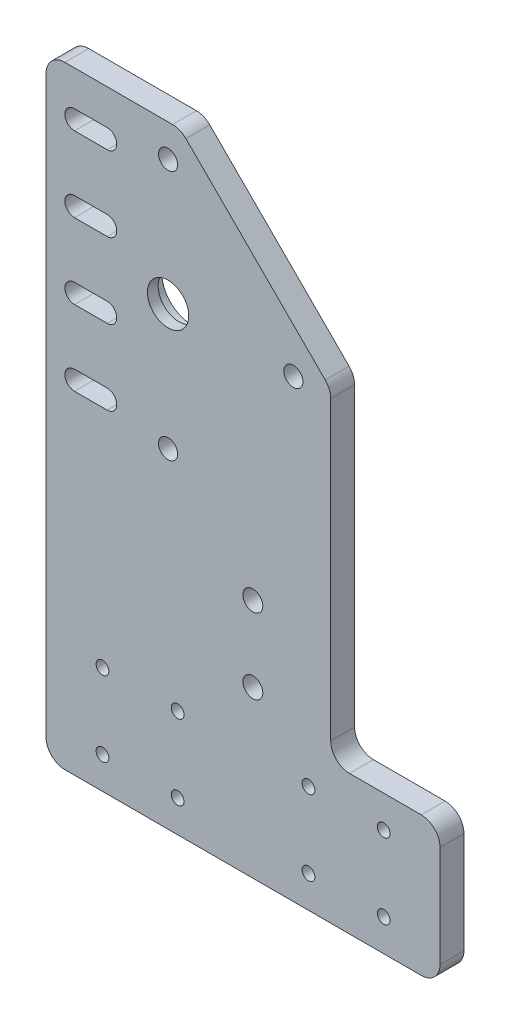
SolidWorks part; units mm, degrees
ref_plane "Alzado" through (0, 0, 0) normal (0, 0, 1) x (1, 0, 0)
ref_plane "Planta" through (0, 0, 0) normal (0, 1, 0) x (1, 0, 0)
ref_plane "Vista lateral" through (0, 0, 0) normal (1, 0, 0) x (0, 0, -1)
sketch "Croquis1" plane through (0, 0, 0) normal (0, 0, 1) x (1, 0, 0)
  line L0 (-57.45, 20) -> (-48.75, 20) construction
  line L1 (-65, -34) -> (-65, 86.95)
  line L3 (10.72, -29) -> (10.72, 49.8789)
  line L4 (15.72, -34) -> (34.8, -34)
  line L5 (34.8, -71) -> (-60, -71)
  line L6 (-50, -62.5) -> (-30, -62.5) construction
  line L7 (-50, -62.5) -> (-50, -42.5) construction
  line L8 (-50, -42.5) -> (-30, -42.5) construction
  line L9 (-30, -62.5) -> (-30, -42.5) construction
  line L10 (-50, -62.5) -> (-30, -42.5) construction
  line L11 (-50, -42.5) -> (-30, -62.5) construction
  line L12 (4.8, -62.5) -> (24.8, -62.5) construction
  line L13 (4.8, -62.5) -> (4.8, -42.5) construction
  line L14 (4.8, -42.5) -> (24.8, -42.5) construction
  line L15 (24.8, -62.5) -> (24.8, -42.5) construction
  line L16 (4.8, -62.5) -> (24.8, -42.5) construction
  line L17 (4.8, -42.5) -> (24.8, -62.5) construction
  line L18 (0, -34) -> (-33, -34) construction
  line L19 (0, -34) -> (0, 0) construction
  line L20 (0, 0) -> (-33, 0) construction
  line L21 (-33, -34) -> (-33, 0) construction
  line L24 (-57.45, 22.55) -> (-48.75, 22.55)
  line L29 (-65, -34) -> (-65, -66)
  line L30 (39.8, -39) -> (39.8, -66)
  line L31 (-57.45, 17.45) -> (-48.75, 17.45)
  line L32 (-57.45, 80) -> (-48.75, 80) construction
  line L33 (-57.45, 82.55) -> (-48.75, 82.55)
  line L34 (-57.45, 77.45) -> (-48.75, 77.45)
  line L35 (-60, 91.95) -> (-31.3511, 91.95)
  line L36 (-27.8155, 90.4855) -> (9.2555, 53.4145)
  line L37 (-57.45, 60) -> (-48.75, 60) construction
  line L38 (-57.45, 62.55) -> (-48.75, 62.55)
  line L39 (-57.45, 57.45) -> (-48.75, 57.45)
  line L40 (-57.45, 40) -> (-48.75, 40) construction
  line L41 (-57.45, 42.55) -> (-48.75, 42.55)
  line L42 (-57.45, 37.45) -> (-48.75, 37.45)
  line L43 (-32.55, 16.667) -> (-32.55, 83.333) construction
  line L44 (-32.55, 16.667) -> (0.783, 50) construction
  line L45 (0.783, 50) -> (-32.55, 83.333) construction
  line L46 (-32.55, 50) -> (0.783, 50) construction
  circle A0 centre (-50, -42.5) radius 1.7
  circle A1 centre (-30, -42.5) radius 1.7
  circle A2 centre (-30, -62.5) radius 1.7
  circle A3 centre (-50, -62.5) radius 1.7
  circle A4 centre (4.8, -62.5) radius 1.7
  circle A5 centre (4.8, -42.5) radius 1.7
  circle A6 centre (24.8, -42.5) radius 1.7
  circle A7 centre (24.8, -62.5) radius 1.7
  circle A8 centre (-10, -7) radius 2.65
  circle A9 centre (-10, -27) radius 2.65
  arc A22 (-60, -71) -> (-65, -66) centre (-60, -66) cw
  arc A23 (34.8, -71) -> (39.8, -66) centre (34.8, -66) ccw
  arc A24 (34.8, -34) -> (39.8, -39) centre (34.8, -39) cw
  arc A25 (10.72, -29) -> (15.72, -34) centre (15.72, -29) ccw
  arc A26 (-57.45, 22.55) -> (-57.45, 17.45) centre (-57.45, 20) ccw
  arc A27 (-48.75, 17.45) -> (-48.75, 22.55) centre (-48.75, 20) ccw
  arc A28 (-57.45, 82.55) -> (-57.45, 77.45) centre (-57.45, 80) ccw
  arc A29 (-48.75, 77.45) -> (-48.75, 82.55) centre (-48.75, 80) ccw
  circle A30 centre (-32.55, 50) radius 5.5
  circle A31 centre (-32.55, 16.667) radius 2.55
  circle A32 centre (-32.55, 83.333) radius 2.55
  circle A33 centre (0.783, 50) radius 2.55
  arc A34 (9.2555, 53.4145) -> (10.72, 49.8789) centre (5.72, 49.8789) cw
  arc A35 (-27.8155, 90.4855) -> (-31.3511, 91.95) centre (-31.3511, 86.95) ccw
  arc A36 (-65, 86.95) -> (-60, 91.95) centre (-60, 86.95) cw
  arc A37 (-57.45, 62.55) -> (-57.45, 57.45) centre (-57.45, 60) ccw
  arc A38 (-48.75, 57.45) -> (-48.75, 62.55) centre (-48.75, 60) ccw
  arc A39 (-57.45, 42.55) -> (-57.45, 37.45) centre (-57.45, 40) ccw
  arc A40 (-48.75, 37.45) -> (-48.75, 42.55) centre (-48.75, 40) ccw
  point P36 (-53.1, 20)
  point P41 (-53.1, 80)
  point P51 (25.26, -34)
  point P52 (-40, -52.5)
  point P58 (14.8, -52.5)
  point P62 (-65, -34)
  point P69 (10.72, 51.95)
  point P70 (10.72, 91.95)
  point P73 (-29.28, 91.95)
  point P76 (-65, 91.95)
  point P78 (-53.1, 60)
  point P85 (-53.1, 40)
  dimension "D3" = 3.4
  dimension "D9" = 5.3
  dimension "D11" = 37
  dimension "D28" = 45
  dimension "D29" = 5
  dimension "D33" = 5
  dimension "D34" = 45
  dimension "D15" = 2.55
  dimension "D20" = 11
  dimension "D36" = 5.1
  dimension "D10" = 5
  dimension "D38" = 5
  dimension "D30" = 20
  dimension "D1" = 125.95
  dimension "D4" = 33
  dimension "D5" = 34
  dimension "D6" = 10
  dimension "D7" = 10
  dimension "D8" = 7
  dimension "D12" = 104.8
  dimension "D13" = 7.55
  dimension "D14" = 8.7
  dimension "D16" = 20
  dimension "D17" = 37
  dimension "D18" = 60
  dimension "D19" = 18.5
  dimension "D21" = 30
  dimension "D22" = 55
  dimension "D23" = 20
  dimension "D24" = 20
  dimension "D25" = 20
  dimension "D26" = 20
  dimension "D27" = 16.2
  dimension "D31" = 25
  dimension "D32" = 25
  dimension "D35" = 47.14
  dimension "D37" = 43.27
  dimension "D39" = 20
  dimension "D40" = 20
extrude "Extrude 1" add sketch "Croquis1" along normal blind 6.35
sketch "Croquis2" plane through (0, 0, 6.35) normal (0, 0, 1) x (1, 0, 0)
  circle A1 centre (-32.55, 50) radius 8.025
  dimension "D1" = 16.05
extrude "Extrude Cut 1" cut sketch "Croquis2" along normal blind 3.5 from surface at -6.35 starting at face at (-30, 83.333, 0)
mirror "Mirror1" [suppressed]
delete or keep bodies "Body-Delete/Keep 1" [suppressed] type delete bodies bodies 102
